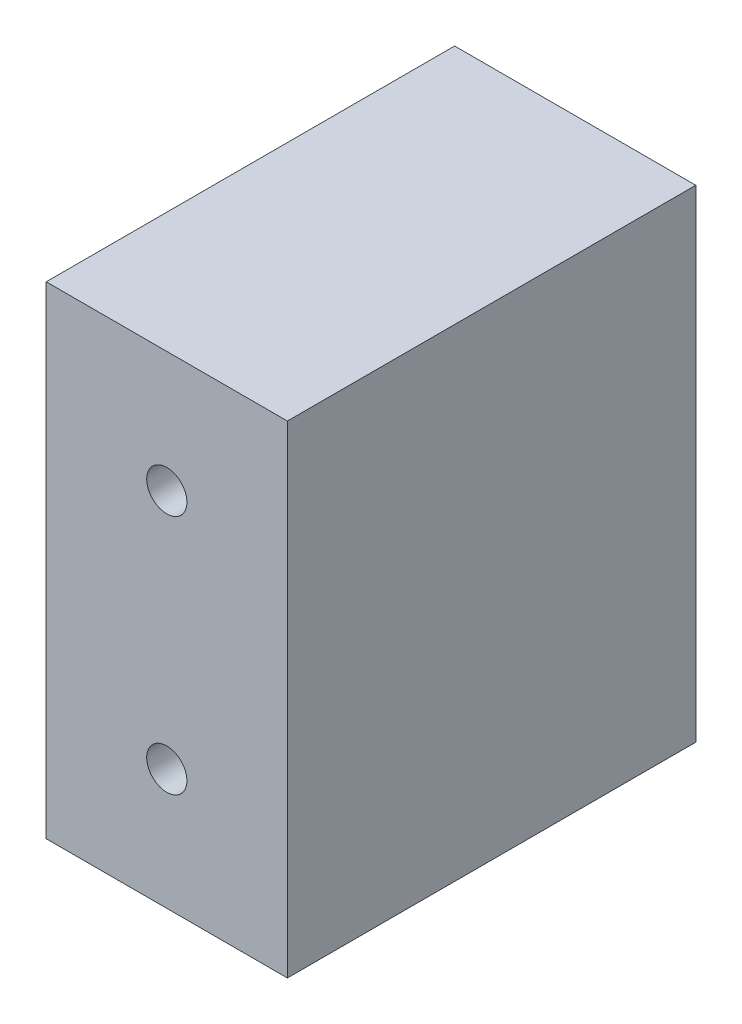
SolidWorks part; units mm, degrees
ref_plane "Front Plane" through (0, 0, 0) normal (0, 0, 1) x (1, 0, 0)
ref_plane "Top Plane" through (0, 0, 0) normal (0, 1, 0) x (1, 0, 0)
ref_plane "Right Plane" through (0, 0, 0) normal (1, 0, 0) x (0, 0, -1)
sketch "Sketch1" plane through (0, 0, 0) normal (0, 0, 1) x (1, 0, 0)
  line L1 (-6.6188, 6.8342) -> (8.3812, 6.8342)
  line L2 (-6.6188, 6.8342) -> (-6.6188, -23.1658)
  line L3 (-6.6188, -23.1658) -> (8.3812, -23.1658)
  line L4 (8.3812, 6.8342) -> (8.3812, -23.1658)
  circle A0 centre (0.8812, -0.6658) radius 1.25
  circle A1 centre (0.8812, -15.6658) radius 1.25
  dimension "D3" = 7.5
  dimension "D1" = 15
  dimension "D2" = 30
  dimension "D4" = 7.5
  dimension "D5" = 7.5
  dimension "D6" = 7.5
extrude "Boss-Extrude1" add sketch "Sketch1" along normal blind 25.4
